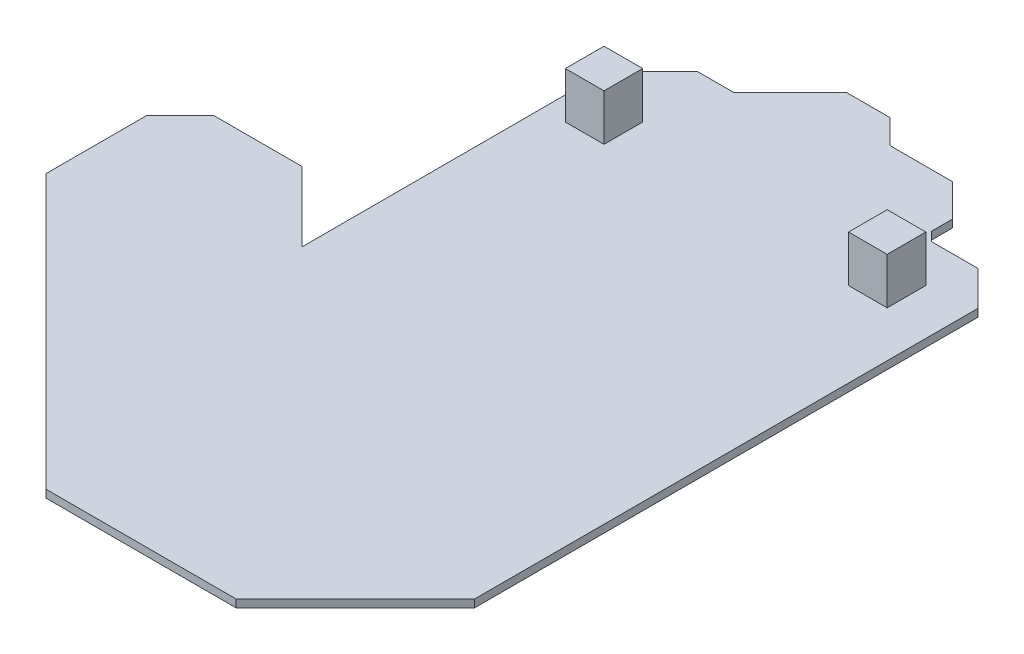
SolidWorks part; units mm, degrees
ref_plane "Plano frontal" through (0, 0, 0) normal (0, 0, 1) x (1, 0, 0)
ref_plane "Plano superior" through (0, 0, 0) normal (0, 1, 0) x (1, 0, 0)
ref_plane "Plano direito" through (0, 0, 0) normal (1, 0, 0) x (0, 0, -1)
sketch "Esboço1" plane through (0, 0, 0) normal (0, 1, 0) x (1, 0, 0)
  line L0 (-21.7959, 4.7833) -> (-12.8081, -4.2045)
  line L1 (-12.8081, 35.1234) -> (-6.9129, 41.0187)
  line L2 (-6.9129, 41.0187) -> (-2.1857, 41.0187)
  line L3 (-2.1857, 41.0187) -> (5.1113, 48.3157)
  line L4 (5.1113, 48.3157) -> (10.7336, 48.3157)
  line L5 (10.7336, 48.3157) -> (13.8722, 45.1772)
  line L6 (13.8722, 45.1772) -> (21.9624, 45.1772)
  line L7 (21.9624, 45.1772) -> (26.175, 40.9646)
  line L8 (26.175, 40.9646) -> (26.175, 38.2756)
  line L9 (26.175, 38.2756) -> (27.3503, 37.1003)
  line L10 (27.3503, 37.1003) -> (33.3571, 37.1003)
  line L11 (33.3571, 37.1003) -> (37.8255, 32.6319)
  line L12 (37.8255, 32.6319) -> (37.8255, -32.5062)
  line L13 (37.8255, -32.5062) -> (22.3699, -47.9619)
  line L14 (22.3699, -47.9619) -> (-2.2114, -47.9619)
  line L15 (-2.2114, -47.9619) -> (-37.5859, -12.5875)
  line L16 (-37.5859, -12.5875) -> (-37.5859, 0.4472)
  line L17 (-37.5859, 0.4472) -> (-33.2497, 4.7833)
  line L18 (-33.2497, 4.7833) -> (-21.7959, 4.7833)
  line L19 (-12.8081, 35.1234) -> (-12.8081, -4.2045)
extrude "Ressalto-extrusão1" add sketch "Esboço1" along normal blind 1
sketch "Esboço2" plane through (0, 1, 0) normal (0, 1, 0) x (1, 0, 0)
  line L5 (31.8964, 31.8063) -> (26.8964, 31.8063)
  line L6 (31.8964, 31.8063) -> (31.8964, 26.8063)
  line L7 (31.8964, 26.8063) -> (26.8964, 26.8063)
  line L8 (26.8964, 31.8063) -> (26.8964, 26.8063)
  line L9 (-9.755, 31.8063) -> (-4.755, 31.8063)
  line L10 (-9.755, 31.8063) -> (-9.755, 26.8063)
  line L11 (-9.755, 26.8063) -> (-4.755, 26.8063)
  line L12 (-4.755, 31.8063) -> (-4.755, 26.8063)
  dimension "D1" = 5
  dimension "D2" = 5
  dimension "D3" = 5
extrude "Ressalto-extrusão2" add sketch "Esboço2" along normal blind 6
